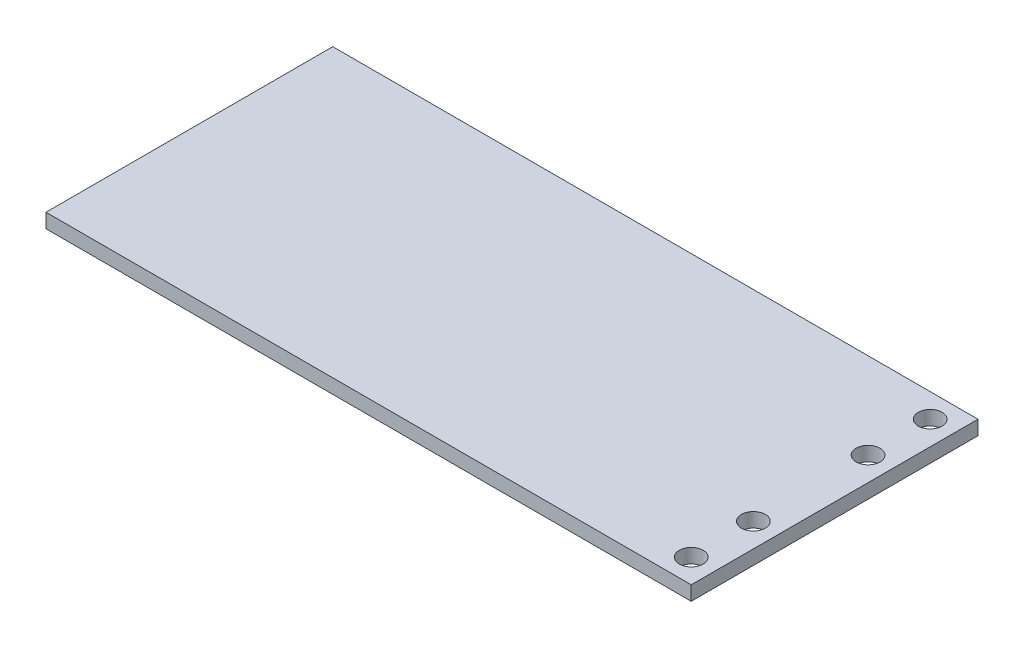
SolidWorks part; units mm, degrees
ref_plane "Front Plane" through (0, 0, 0) normal (0, 0, 1) x (1, 0, 0)
ref_plane "Top Plane" through (0, 0, 0) normal (0, 1, 0) x (1, 0, 0)
ref_plane "Right Plane" through (0, 0, 0) normal (1, 0, 0) x (0, 0, -1)
sketch "Sketch1" plane through (0, 0, 0) normal (0, 1, 0) x (1, 0, 0)
  line L0 (130, 60) -> (130, 0) construction
  line L1 (0, 0) -> (135, 0)
  line L2 (0, 0) -> (0, 60)
  line L3 (0, 60) -> (135, 60)
  line L4 (135, 0) -> (135, 60)
  circle A0 centre (130, 42) radius 2.5
  circle A2 centre (130, 18) radius 2.5
  circle A3 centre (130, 5) radius 2.5
  circle A4 centre (130, 55) radius 2.5
  point P15 (130, 44.5)
  point P17 (130, 7.5)
  dimension "D8" = 5
  dimension "D1" = 135
  dimension "D2" = 60
  dimension "D3" = 5
  dimension "D4" = 18
  dimension "D5" = 5
  dimension "D6" = 13
  dimension "D7" = 5
extrude "Boss-Extrude1" add sketch "Sketch1" along normal blind 3 contours L0 L3 L2 L1 A3 A2 A0 A4 | L3 L0 A4 A0 A2 A3 L1 L4
sketch "Sketch2" plane through (0, 3, 0) normal (0, 1, 0) x (1, 0, 0)
  line L1 (50, 19.5563) -> (85, 19.5563)
  line L2 (50, 19.5563) -> (50, 54.5563)
  line L3 (50, 54.5563) -> (85, 54.5563)
  line L4 (85, 19.5563) -> (85, 54.5563)
  line L6 (67.5, 60) -> (67.5, 54.5563) construction
  line L7 (0, 60) -> (135, 60) construction
  point P11 (67.5, 54.5563)
  point P18 (67.5, 60)
  dimension "D2" = 35
